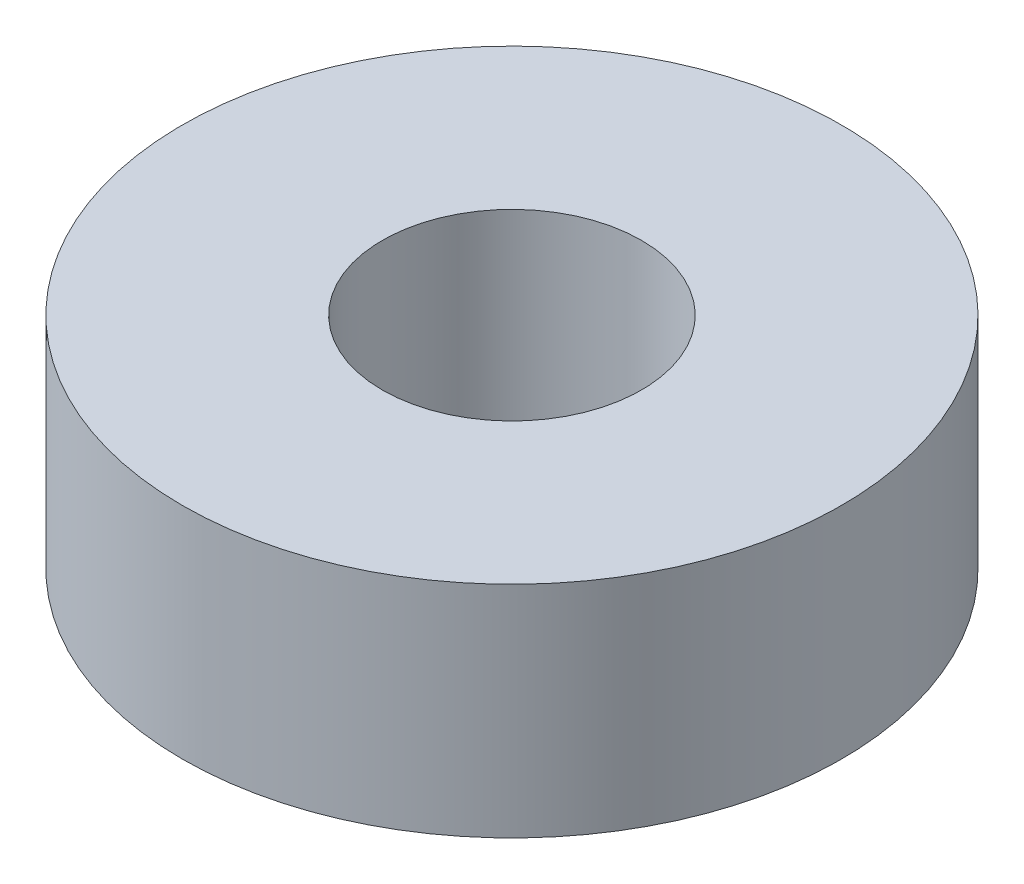
SolidWorks part; units mm, degrees
material "Galvanized Steel"
ref_plane "Front Plane" through (0, 0, 0) normal (0, 0, 1) x (1, 0, 0)
ref_plane "Top Plane" through (0, 0, 0) normal (0, 1, 0) x (1, 0, 0)
ref_plane "Right Plane" through (0, 0, 0) normal (1, 0, 0) x (0, 0, -1)
sketch "Sketch1" plane through (0, 0, 0) normal (0, 1, 0) x (1, 0, 0)
  circle A0 centre (0, 0) radius 7.5
  circle A1 centre (0, 0) radius 2.95
  dimension "D1" = 15
  dimension "D2" = 5.9
extrude "Boss-Extrude1" add sketch "Sketch1" along normal blind 5
